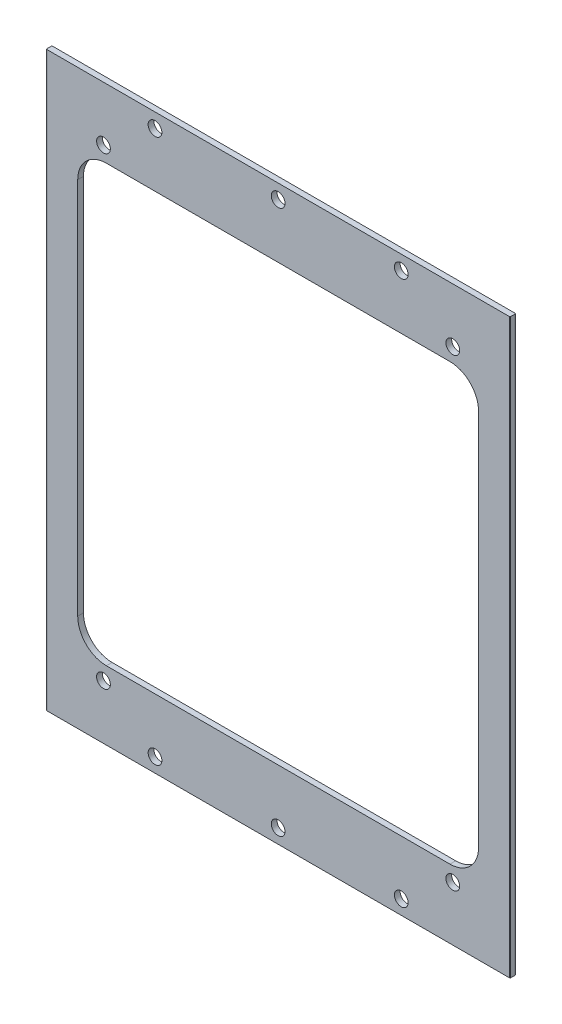
SolidWorks part; units mm, degrees
material "6061 Alloy"
ref_plane "Frontal" through (0, 0, 0) normal (0, 0, 1) x (1, 0, 0)
ref_plane "Superior" through (0, 0, 0) normal (0, 1, 0) x (1, 0, 0)
ref_plane "Direito" through (0, 0, 0) normal (1, 0, 0) x (0, 0, -1)
sketch "Sketch1" plane through (0, 0, 0) normal (0, 0, 1) x (1, 0, 0)
  line L1 (-40.5, -50) -> (40.5, -50)
  line L2 (-40.5, -50) -> (-40.5, 50)
  line L3 (-40.5, 50) -> (40.5, 50)
  line L4 (40.5, -50) -> (40.5, 50)
  line L5 (-40.5, -50) -> (40.5, 50) construction
  line L6 (-40.5, 50) -> (40.5, -50) construction
  point P0 (0, 0)
  dimension "D1" = 100
  dimension "D2" = 81
extrude "Boss-Extrude1" add sketch "Sketch1" along normal mid plane 1
sketch "Sketch2" plane through (0, 0, 0.5) normal (0, 0, 1) x (1, 0, 0)
  line L1 (-30, -38) -> (30, -38)
  line L2 (-35, -33) -> (-35, 33)
  line L3 (-30, 38) -> (30, 38)
  line L4 (35, -33) -> (35, 33)
  line L5 (-30, -33) -> (30, 33) construction
  line L6 (-30, 33) -> (30, -33) construction
  arc A0 (-35, 33) -> (-30, 38) centre (-30, 33) cw
  arc A1 (30, 38) -> (35, 33) centre (30, 33) cw
  arc A2 (35, -33) -> (30, -38) centre (30, -33) cw
  arc A3 (-30, -38) -> (-35, -33) centre (-30, -33) cw
  point P0 (0, 0)
  dimension "D1" = 5
  dimension "D2" = 5
  dimension "D3" = 5
  dimension "D4" = 5
  dimension "D5" = 70
  dimension "D6" = 76
extrude "Cut-Extrude1" cut sketch "Sketch2" against normal through all
hole_wizard "M2 Hole1 - AD" positions "Sketch4" profile "Sketch3" hole size "M2" standard "DIN"
sketch "Sketch4" plane through (0, 0, 0.5) normal (0, 0, 1) x (1, 0, 0)
  line L0 (30, 38) -> (-30, 38) construction
  line L1 (-30, -38) -> (30, -38) construction
  line L2 (-40.5, 50) -> (-40.5, -50) construction
  line L3 (40.5, -50) -> (40.5, 50) construction
  point P0 (-30.5, 40.5)
  point P2 (30.5, 40.5)
  point P4 (-30.5, -40.5)
  point P6 (30.5, -40.5)
  dimension "D1" = 2.5
  dimension "D2" = 2.5
  dimension "D3" = 10
  dimension "D4" = 10
sketch "Sketch3" plane through (-30.5, 40.5, 0.5) normal (1, 0, 0) x (0, -1, 0)
  line L0 (0, 0) -> (0, 100.721)
  line L1 (0, 100.721) -> (1.2, 100)
  line L2 (1.2, 100) -> (1.2, 0)
  line L5 (1.2, 0) -> (0, 0)
  line L10 (0, 100.721) -> (-1.2, 100) construction
  line L11 (0, -6.35) -> (0, 107.95) construction
  dimension "Hole Dia." = 2.4
  dimension "Hole Depth" = 100
  dimension "Drill Angle" = 118
hole_wizard "M2 Hole2 - AD" positions "Sketch6" profile "Sketch5" hole size "M2" standard "DIN"
sketch "Sketch6" plane through (0, 0, 0.5) normal (0, 0, 1) x (1, 0, 0)
  line L0 (40.5, 50) -> (-40.5, 50) construction
  line L1 (-40.5, -50) -> (40.5, -50) construction
  line L2 (-40.5, 50) -> (-40.5, -50) construction
  line L3 (40.5, -50) -> (40.5, 50) construction
  point P0 (-21.5, 47.5)
  point P2 (21.5, 47.5)
  point P4 (-21.5, -47.5)
  point P6 (21.5, -47.5)
  dimension "D1" = 2.5
  dimension "D2" = 2.5
  dimension "D3" = 19
  dimension "D4" = 19
sketch "Sketch5" plane through (-21.5, 47.5, 0.5) normal (1, 0, 0) x (0, -1, 0)
  line L0 (0, 0) -> (0, 100.721)
  line L1 (0, 100.721) -> (1.2, 100)
  line L2 (1.2, 100) -> (1.2, 0)
  line L5 (1.2, 0) -> (0, 0)
  line L10 (0, 100.721) -> (-1.2, 100) construction
  line L11 (0, -6.35) -> (0, 107.95) construction
  dimension "Hole Dia." = 2.4
  dimension "Hole Depth" = 100
  dimension "Drill Angle" = 118
hole_wizard "M2 Hole3 - AE" positions "Sketch8" profile "Sketch7" hole size "M2" standard "DIN"
sketch "Sketch8" plane through (0, 0, 0.5) normal (0, 0, 1) x (1, 0, 0)
  line L0 (-40.5, -50) -> (40.5, -50) construction
  line L1 (40.5, 50) -> (-40.5, 50) construction
  point P0 (0, 47.5)
  point P2 (0, -47.5)
  dimension "D1" = 2.5
  dimension "D2" = 2.5
sketch "Sketch7" plane through (0, 47.5, 0.5) normal (1, 0, 0) x (0, -1, 0)
  line L0 (0, 0) -> (0, 200.721)
  line L1 (0, 200.721) -> (1.2, 200)
  line L2 (1.2, 200) -> (1.2, 0)
  line L5 (1.2, 0) -> (0, 0)
  line L10 (0, 200.721) -> (-1.2, 200) construction
  line L11 (0, -6.35) -> (0, 107.95) construction
  dimension "Hole Dia." = 2.4
  dimension "Hole Depth" = 200
  dimension "Drill Angle" = 118
fillet "Fillet1" radius 0.1 4 edges at (40.5, 0, -0.5) (40.5, 0, 0.5) (-40.5, 0, -0.5) (-40.5, 0, 0.5)
